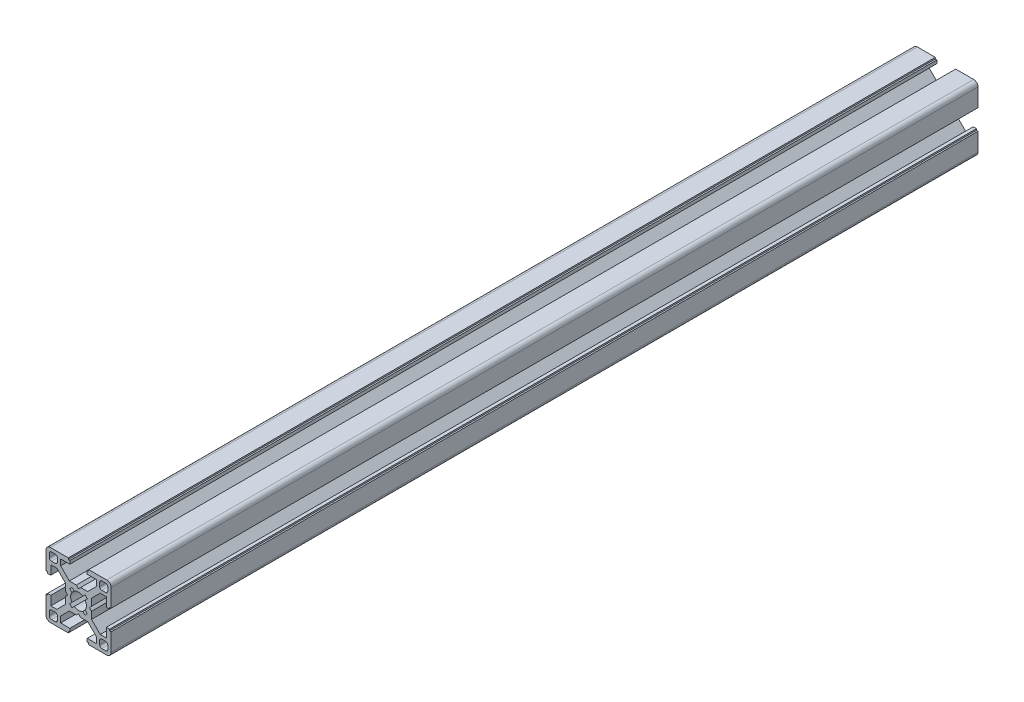
SolidWorks part; units mm, degrees
material "6063-O, Barra estrusa (SS)"
ref_plane "Piano frontale" through (0, 0, 0) normal (0, 0, 1) x (1, 0, 0)
ref_plane "Piano superiore" through (0, 0, 0) normal (0, 1, 0) x (1, 0, 0)
ref_plane "Piano destro" through (0, 0, 0) normal (1, 0, 0) x (0, 0, -1)
sketch "Schizzo1" plane through (0, 0, 0) normal (0, 0, 1) x (1, 0, 0)
  line L0 (-125.0647, 0) -> (53.776, 0) construction
  line L1 (0, -44.8297) -> (0, 95.2781) construction
  line L2 (-15, 13) -> (-15, 4.7)
  line L3 (-15, 4.7) -> (-14.3, 4.7)
  line L4 (-14.3, 4.7) -> (-14.3, 4)
  line L5 (-14.3, 4) -> (-12.8, 4)
  line L6 (-12.8, 4) -> (-12.8, 8.25)
  line L7 (-12.8, 8.25) -> (-10.0178, 8.25)
  line L8 (-10.0178, 8.25) -> (-6, 4.2322)
  line L9 (-6, 4.2322) -> (-6, 1)
  line L10 (-6, 1) -> (-5, 0)
  line L11 (-1, 6) -> (0, 5)
  line L12 (0, 0) -> (-161.3113, 161.3113) construction
  line L13 (-4.2322, 6) -> (-1, 6)
  line L14 (-8.25, 10.0178) -> (-4.2322, 6)
  line L15 (-8.25, 12.8) -> (-8.25, 10.0178)
  line L16 (-4, 12.8) -> (-8.25, 12.8)
  line L17 (-4, 14.3) -> (-4, 12.8)
  line L18 (-4.7, 14.3) -> (-4, 14.3)
  line L19 (-4.7, 15) -> (-4.7, 14.3)
  line L20 (-13, 15) -> (-4.7, 15)
  line L21 (13.5, 10.75) -> (13.5, 12.5)
  line L22 (10.75, 13.5) -> (12.5, 13.5)
  line L23 (9.75, 10.75) -> (9.75, 12.5)
  line L24 (10.75, 9.75) -> (12.5, 9.75)
  line L25 (10.75, -13.5) -> (12.5, -13.5)
  line L26 (13.5, -10.75) -> (13.5, -12.5)
  line L27 (10.75, -9.75) -> (12.5, -9.75)
  line L28 (9.75, -10.75) -> (9.75, -12.5)
  line L29 (-13.5, -10.75) -> (-13.5, -12.5)
  line L30 (-10.75, -13.5) -> (-12.5, -13.5)
  line L31 (-9.75, -10.75) -> (-9.75, -12.5)
  line L32 (-10.75, -9.75) -> (-12.5, -9.75)
  line L33 (1.9955, 3.0562) -> (3.0052, 4.0659)
  line L34 (3.0052, 4.0659) -> (4.0659, 3.0052)
  line L35 (4.0659, 3.0052) -> (3.0562, 1.9955)
  line L36 (3.0562, -1.9955) -> (4.0659, -3.0052)
  line L37 (4.0659, -3.0052) -> (3.0052, -4.0659)
  line L38 (3.0052, -4.0659) -> (1.9955, -3.0562)
  line L39 (-1.9955, -3.0562) -> (-3.0052, -4.0659)
  line L40 (-3.0052, -4.0659) -> (-4.0659, -3.0052)
  line L41 (-4.0659, -3.0052) -> (-3.0562, -1.9955)
  line L42 (1, 6) -> (0, 5)
  line L43 (4.2322, 6) -> (1, 6)
  line L44 (8.25, 10.0178) -> (4.2322, 6)
  line L45 (8.25, 12.8) -> (8.25, 10.0178)
  line L46 (4, 12.8) -> (8.25, 12.8)
  line L47 (12.8, 4) -> (12.8, 8.25)
  line L48 (12.8, 8.25) -> (10.0178, 8.25)
  line L49 (10.0178, 8.25) -> (6, 4.2322)
  line L50 (6, 4.2322) -> (6, 1)
  line L51 (6, 1) -> (5, 0)
  line L52 (6, -1) -> (5, 0)
  line L53 (6, -4.2322) -> (6, -1)
  line L54 (10.0178, -8.25) -> (6, -4.2322)
  line L55 (12.8, -8.25) -> (10.0178, -8.25)
  line L56 (12.8, -4) -> (12.8, -8.25)
  line L57 (4, -12.8) -> (8.25, -12.8)
  line L58 (8.25, -12.8) -> (8.25, -10.0178)
  line L59 (8.25, -10.0178) -> (4.2322, -6)
  line L60 (4.2322, -6) -> (1, -6)
  line L61 (1, -6) -> (0, -5)
  line L62 (-1, -6) -> (0, -5)
  line L63 (-4.2322, -6) -> (-1, -6)
  line L64 (-8.25, -10.0178) -> (-4.2322, -6)
  line L65 (-8.25, -12.8) -> (-8.25, -10.0178)
  line L66 (-4, -12.8) -> (-8.25, -12.8)
  line L67 (-12.8, -4) -> (-12.8, -8.25)
  line L68 (-12.8, -8.25) -> (-10.0178, -8.25)
  line L69 (-10.0178, -8.25) -> (-6, -4.2322)
  line L70 (-6, -4.2322) -> (-6, -1)
  line L71 (-6, -1) -> (-5, 0)
  line L72 (4, 14.3) -> (4, 12.8)
  line L73 (4.7, 14.3) -> (4, 14.3)
  line L74 (4.7, 15) -> (4.7, 14.3)
  line L75 (-3.0562, 1.9955) -> (-4.0659, 3.0052)
  line L76 (-4.0659, 3.0052) -> (-3.0052, 4.0659)
  line L77 (-3.0052, 4.0659) -> (-1.9955, 3.0562)
  line L78 (15, 4.7) -> (14.3, 4.7)
  line L79 (-10.75, 9.75) -> (-12.5, 9.75)
  line L80 (-9.75, 10.75) -> (-9.75, 12.5)
  line L81 (-10.75, 13.5) -> (-12.5, 13.5)
  line L82 (-13.5, 10.75) -> (-13.5, 12.5)
  line L83 (14.3, 4.7) -> (14.3, 4)
  line L84 (14.3, 4) -> (12.8, 4)
  line L85 (14.3, -4) -> (12.8, -4)
  line L86 (14.3, -4.7) -> (14.3, -4)
  line L87 (15, -4.7) -> (14.3, -4.7)
  line L88 (4.7, -15) -> (4.7, -14.3)
  line L89 (4.7, -14.3) -> (4, -14.3)
  line L90 (4, -14.3) -> (4, -12.8)
  line L91 (-4, -14.3) -> (-4, -12.8)
  line L92 (-4.7, -14.3) -> (-4, -14.3)
  line L93 (-4.7, -15) -> (-4.7, -14.3)
  line L94 (-15, -4.7) -> (-14.3, -4.7)
  line L95 (-14.3, -4.7) -> (-14.3, -4)
  line L96 (-14.3, -4) -> (-12.8, -4)
  line L97 (4, 14.3) -> (4, 12.8)
  line L98 (4.7, 14.3) -> (4, 14.3)
  line L99 (4.7, 15) -> (4.7, 14.3)
  line L100 (15, 4.7) -> (14.3, 4.7)
  line L101 (14.3, 4.7) -> (14.3, 4)
  line L102 (14.3, 4) -> (12.8, 4)
  line L103 (13, 15) -> (4.7, 15)
  line L104 (15, 13) -> (15, 4.7)
  line L105 (14.3, -4) -> (12.8, -4)
  line L106 (14.3, -4.7) -> (14.3, -4)
  line L107 (15, -4.7) -> (14.3, -4.7)
  line L108 (4.7, -15) -> (4.7, -14.3)
  line L109 (4.7, -14.3) -> (4, -14.3)
  line L110 (4, -14.3) -> (4, -12.8)
  line L111 (15, -13) -> (15, -4.7)
  line L112 (13, -15) -> (4.7, -15)
  line L113 (-4, -14.3) -> (-4, -12.8)
  line L114 (-4.7, -14.3) -> (-4, -14.3)
  line L115 (-4.7, -15) -> (-4.7, -14.3)
  line L116 (-15, -4.7) -> (-14.3, -4.7)
  line L117 (-14.3, -4.7) -> (-14.3, -4)
  line L118 (-14.3, -4) -> (-12.8, -4)
  line L119 (-13, -15) -> (-4.7, -15)
  line L120 (-15, -13) -> (-15, -4.7)
  arc A0 (-3.65, 0) -> (-3.0562, 1.9955) centre (0, 0) cw
  arc A1 (-1.9955, 3.0562) -> (0, 3.65) centre (0, 0) cw
  arc A2 (-13, 15) -> (-15, 13) centre (-13, 13) ccw
  arc A3 (-13.5, 10.75) -> (-12.5, 9.75) centre (-12.5, 10.75) ccw
  arc A4 (-9.75, 10.75) -> (-10.75, 9.75) centre (-10.75, 10.75) cw
  arc A5 (-10.75, 13.5) -> (-9.75, 12.5) centre (-10.75, 12.5) cw
  arc A6 (-12.5, 13.5) -> (-13.5, 12.5) centre (-12.5, 12.5) ccw
  arc A7 (13.5, 12.5) -> (12.5, 13.5) centre (12.5, 12.5) ccw
  arc A8 (13.5, 10.75) -> (12.5, 9.75) centre (12.5, 10.75) cw
  arc A9 (10.75, 9.75) -> (9.75, 10.75) centre (10.75, 10.75) cw
  arc A10 (10.75, 13.5) -> (9.75, 12.5) centre (10.75, 12.5) ccw
  arc A11 (12.5, -13.5) -> (13.5, -12.5) centre (12.5, -12.5) ccw
  arc A12 (10.75, -13.5) -> (9.75, -12.5) centre (10.75, -12.5) cw
  arc A13 (9.75, -10.75) -> (10.75, -9.75) centre (10.75, -10.75) cw
  arc A14 (13.5, -10.75) -> (12.5, -9.75) centre (12.5, -10.75) ccw
  arc A15 (-13.5, -12.5) -> (-12.5, -13.5) centre (-12.5, -12.5) ccw
  arc A16 (-13.5, -10.75) -> (-12.5, -9.75) centre (-12.5, -10.75) cw
  arc A17 (-10.75, -9.75) -> (-9.75, -10.75) centre (-10.75, -10.75) cw
  arc A18 (-10.75, -13.5) -> (-9.75, -12.5) centre (-10.75, -12.5) ccw
  arc A19 (0, 3.65) -> (1.9955, 3.0562) centre (0, 0) cw
  arc A20 (3.0562, 1.9955) -> (3.65, 0) centre (0, 0) cw
  arc A21 (3.65, 0) -> (3.0562, -1.9955) centre (0, 0) cw
  arc A22 (1.9955, -3.0562) -> (0, -3.65) centre (0, 0) cw
  arc A23 (0, -3.65) -> (-1.9955, -3.0562) centre (0, 0) cw
  arc A24 (-3.0562, -1.9955) -> (-3.65, 0) centre (0, 0) cw
  arc A25 (15, 13) -> (13, 15) centre (13, 13) ccw
  arc A26 (13, -15) -> (15, -13) centre (13, -13) ccw
  arc A27 (-15, -13) -> (-13, -15) centre (-13, -13) ccw
  point P70 (0, 0)
  point P86 (0, 0)
  point P88 (-15, 15)
  point P100 (-9.75, 9.75)
  point P107 (0, 0)
  point P144 (0, 0)
  point P169 (0, 0)
  point P197 (0, 0)
  dimension "D11" = 7.3
  dimension "D14" = 2
  dimension "D17" = 1
  dimension "D1" = 45
  dimension "D2" = 8
  dimension "D3" = 16.5
  dimension "D4" = 9
  dimension "D5" = 2.2
  dimension "D6" = 15
  dimension "D7" = 2.5
  dimension "D8" = 8.3
  dimension "D9" = 2
  dimension "D12" = 5
  dimension "D13" = 1.5
  dimension "D15" = 1.5
  dimension "D16" = 1.5
  dimension "D10" = 4
  dimension "D18" = 4
  dimension "D19" = 4
  dimension "D20" = 4
  dimension "D21" = 4
extrude "Estrusione-Estrusione2" add sketch "Schizzo1" along normal blind 400 contours L120 A27 L119 L93 L92 L91 L66 L65 L64 L63 L62 L61 L60 L59 L58 L57 L90 L89 L88 L112 A26 L111 L87 L86 L85 L56 L55 L54 L53 L52 L51 L50 L49 L48 L47 L84 L83 L78 L104 A25 L103 L74 L73 L72 L46 L45 L44 L43 L42 L11 L13
